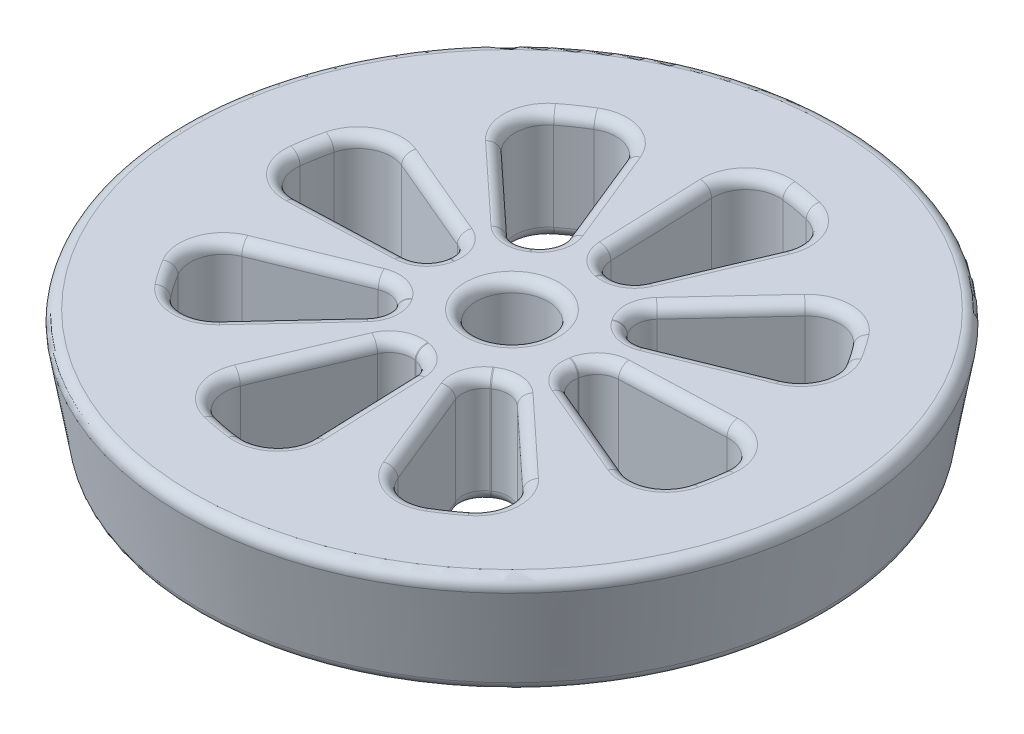
SolidWorks part; units mm, degrees
ref_plane "Front Plane" through (0, 0, 0) normal (0, 0, 1) x (1, 0, 0)
ref_plane "Top Plane" through (0, 0, 0) normal (0, 1, 0) x (1, 0, 0)
ref_plane "Right Plane" through (0, 0, 0) normal (1, 0, 0) x (0, 0, -1)
sketch "草圖1" plane through (0, 0, 0) normal (0, 1, 0) x (1, 0, 0)
  line L0 (-5.5912, 21.2777) -> (-1.9061, 7.2537)
  line L1 (4.3315, 6.1228) -> (12.7057, 17.9601)
  line L2 (0, 0) -> (12.7057, 17.9601) construction
  line L3 (0, 0) -> (-5.5912, 21.2777) construction
  circle A0 centre (0, 0) radius 30
  circle A1 centre (0, 0) radius 22
  circle A2 centre (0, 0) radius 3.25
  circle A3 centre (0, 0) radius 7.5
  arc A4 (-1.9061, 7.2537) -> (4.3315, 6.1228) centre (0, 0) cw
  arc A5 (-5.5912, 21.2777) -> (12.7057, 17.9601) centre (0, 0) ccw
  dimension "D1" = 60
  dimension "D2" = 8
  dimension "D3" = 6.5
  dimension "D4" = 15
  dimension "D5" = 50
extrude "填料-伸長1" add sketch "草圖1" along normal blind 10 contours A0 A1 | A3 A2
sketch "草圖2" plane through (0, 10, 0) normal (0, 1, 0) x (1, 0, 0)
  line L0 (-2.8233, 6.9483) -> (-8.2817, 20.3817)
  line L1 (-0.2766, 7.4949) -> (-0.8113, 21.985)
  line L2 (0, 0) -> (-0.8113, 21.985) construction
  line L3 (0, 0) -> (-8.2817, 20.3817) construction
  line L4 (5.1041, 5.4953) -> (14.9721, 16.1194)
  line L5 (2.9168, 6.9096) -> (8.556, 20.2681)
  line L6 (7.4949, 0.2766) -> (21.985, 0.8113)
  line L7 (6.9483, 2.8233) -> (20.3817, 8.2817)
  line L8 (5.4953, -5.1041) -> (16.1194, -14.9721)
  line L9 (6.9096, -2.9168) -> (20.2681, -8.556)
  line L10 (0.2766, -7.4949) -> (0.8113, -21.985)
  line L11 (2.8233, -6.9483) -> (8.2817, -20.3817)
  line L12 (-5.1041, -5.4953) -> (-14.9721, -16.1194)
  line L13 (-2.9168, -6.9096) -> (-8.556, -20.2681)
  line L14 (-7.4949, -0.2766) -> (-21.985, -0.8113)
  line L15 (-6.9483, -2.8233) -> (-20.3817, -8.2817)
  line L16 (-5.4953, 5.1041) -> (-16.1194, 14.9721)
  line L17 (-6.9096, 2.9168) -> (-20.2681, 8.556)
  circle A0 centre (0, 0) radius 22 construction
  arc A1 (-0.2766, 7.4949) -> (-2.8233, 6.9483) centre (0, 0) ccw
  arc A2 (-0.8113, 21.985) -> (-8.2817, 20.3817) centre (0, 0) ccw
  circle A3 centre (0, 0) radius 7.5 construction
  arc A4 (14.9721, 16.1194) -> (8.556, 20.2681) centre (0, 0) ccw
  arc A5 (5.1041, 5.4953) -> (2.9168, 6.9096) centre (0, 0) ccw
  arc A6 (21.985, 0.8113) -> (20.3817, 8.2817) centre (0, 0) ccw
  arc A7 (7.4949, 0.2766) -> (6.9483, 2.8233) centre (0, 0) ccw
  arc A8 (16.1194, -14.9721) -> (20.2681, -8.556) centre (0, 0) ccw
  arc A9 (5.4953, -5.1041) -> (6.9096, -2.9168) centre (0, 0) ccw
  arc A10 (0.8113, -21.985) -> (8.2817, -20.3817) centre (0, 0) ccw
  arc A11 (0.2766, -7.4949) -> (2.8233, -6.9483) centre (0, 0) ccw
  arc A12 (-14.9721, -16.1194) -> (-8.556, -20.2681) centre (0, 0) ccw
  arc A13 (-5.1041, -5.4953) -> (-2.9168, -6.9096) centre (0, 0) ccw
  arc A14 (-21.985, -0.8113) -> (-20.3817, -8.2817) centre (0, 0) ccw
  arc A15 (-7.4949, -0.2766) -> (-6.9483, -2.8233) centre (0, 0) ccw
  arc A16 (-16.1194, 14.9721) -> (-20.2681, 8.556) centre (0, 0) ccw
  arc A17 (-5.4953, 5.1041) -> (-6.9096, 2.9168) centre (0, 0) ccw
  point P40 (0, 0)
  circle M7 centre (0, 0) radius 22
  dimension "D1" = 20
  dimension "D2" = 8
extrude "填料-伸長3" add sketch "草圖2" against normal through all contours A5 L4 L5 M7 | A1 L1 L0 M7 | A17 L16 L17 M7 | A15 L14 L15 M7 | A13 L12 L13 M7 | A11 L10 L11 M7 | A9 L8 L9 M7 | A7 L6 L7 M7
fillet "圓角1" radius 3 16 edges at (20.2681, 5, 8.556) (16.1194, 5, 14.9721) (20.3817, 5, -8.2817) (8.556, 5, -20.2681) (21.985, 5, -0.8113) (14.9721, 5, -16.1194) (-8.2817, 5, -20.3817) (-0.8113, 5, -21.985) (-20.2681, 5, -8.556) (-16.1194, 5, -14.9721) (-20.3817, 5, 8.2817) (-21.985, 5, 0.8113) (-8.556, 5, 20.2681) (-14.9721, 5, 16.1194) (8.2817, 5, 20.3817) (0.8113, 5, 21.985)
fillet "圓角3" radius 2 16 edges at (-0.2766, 5, -7.4949) (2.9168, 5, -6.9096) (6.9483, 5, -2.8233) (5.1041, 5, -5.4953) (7.4949, 5, -0.2766) (6.9096, 5, 2.9168) (5.4953, 5, 5.1041) (2.8233, 5, 6.9483) (-2.9168, 5, 6.9096) (0.2766, 5, 7.4949) (-6.9483, 5, 2.8233) (-5.1041, 5, 5.4953) (-6.9096, 5, -2.9168) (-7.4949, 5, 0.2766) (-2.8233, 5, -6.9483) (-5.4953, 5, -5.1041)
sketch "草圖3" plane through (0, 10, 0) normal (0, 1, 0) x (1, 0, 0)
  circle A0 centre (0, 0) radius 30
  circle A1 centre (0, 0) radius 58.0891
extrude "除料-伸長1" cut sketch "草圖3" against normal through all draft 10 draft outward yes
fillet "圓角4" radius 1 120 edges at (0, 0, 28.2367) (5.7905, 0, -5.5818) (9.5443, 10, -10.2757) (9.5443, 0, -10.2757) (15.0935, 0, -14.7024) (18.1061, 0, -12.4968) (19.0998, 0, -8.8978) (12.9928, 0, -5.2793) (12.9928, 10, -5.2793) (7.2727, 0, -3.4344) (6.1725, 0, -4.2603) (8.0414, 0, 0.1476) (14.0148, 10, -0.5172) (14.0148, 0, -0.5172) (21.0689, 0, 0.2766) (3.9664, 0, -21.6395) (19.7973, 0, 7.2139) (12.9203, 0, 5.4542) (12.9203, 10, 5.4542) (7.571, 0, 2.7141) (7.3771, 0, 1.3522) (5.5818, 0, 5.7905) (10.2757, 10, 9.5443) (10.2757, 0, 9.5443) (14.7024, 0, 15.0935) (8.8978, 0, 19.0998) (5.2793, 0, 12.9928) (5.2793, 10, 12.9928) (3.4344, 0, 7.2727) (4.2603, 0, 6.1725) (-0.1476, 0, 8.0414) (0.5172, 10, 14.0148) (0.5172, 0, 14.0148) (-0.2766, 0, 21.0689) (-7.2139, 0, 19.7973) (-5.4542, 0, 12.9203) (-5.4542, 10, 12.9203) (-2.7141, 0, 7.571) (-1.3522, 0, 7.3771) (-5.7905, 0, 5.5818) (-9.5443, 10, 10.2757) (-9.5443, 0, 10.2757) (-15.0935, 0, 14.7024) (-19.0998, 0, 8.8978) (-12.9928, 0, 5.2793) (-12.9928, 10, 5.2793) (-7.2727, 0, 3.4344) (-6.1725, 0, 4.2603) (-5.5818, 0, -5.7905) (-10.2757, 10, -9.5443) (-10.2757, 0, -9.5443) (-14.7024, 0, -15.0935) (-8.8978, 0, -19.0998) (-5.2793, 0, -12.9928) (-5.2793, 10, -12.9928) (-3.4344, 0, -7.2727) (-4.2603, 0, -6.1725) (0.1476, 0, -8.0414) (-0.5172, 10, -14.0148) (-0.5172, 0, -14.0148) (0.2766, 0, -21.0689) (7.2139, 0, -19.7973) (5.4542, 0, -12.9203) (5.4542, 10, -12.9203) (2.7141, 0, -7.571) (1.3522, 0, -7.3771) (-8.0414, 0, -0.1476) (-14.0148, 10, 0.5172) (-14.0148, 0, 0.5172) (-21.0689, 0, -0.2766) (-19.7973, 0, -7.2139) (-12.9203, 0, -5.4542) (-12.9203, 10, -5.4542) (-7.571, 0, -2.7141) (-7.3771, 0, -1.3522) (0, 0, 3.25) (0, 10, 3.25) (0, 10, 30) (-21.0689, 10, -0.2766) (-8.0414, 10, -0.1476) (-7.3771, 10, -1.3522) (-7.571, 10, -2.7141) (-19.7973, 10, -7.2139) (18.1061, 10, -12.4968) (3.9664, 10, -21.6395) (2.7141, 10, -7.571) (7.2139, 10, -19.7973) (0.2766, 10, -21.0689) (0.1476, 10, -8.0414) (1.3522, 10, -7.3771) (-3.4344, 10, -7.2727) (-8.8978, 10, -19.0998) (-14.7024, 10, -15.0935) (-5.5818, 10, -5.7905) (-4.2603, 10, -6.1725) (-19.0998, 10, 8.8978) (-15.0935, 10, 14.7024) (-5.7905, 10, 5.5818) (-6.1725, 10, 4.2603) (-7.2727, 10, 3.4344) (-7.2139, 10, 19.7973) (-0.2766, 10, 21.0689) (-0.1476, 10, 8.0414) (-1.3522, 10, 7.3771) (-2.7141, 10, 7.571) (8.8978, 10, 19.0998) (14.7024, 10, 15.0935) (5.5818, 10, 5.7905) (4.2603, 10, 6.1725) (3.4344, 10, 7.2727) (19.7973, 10, 7.2139) (21.0689, 10, 0.2766) (8.0414, 10, 0.1476) (7.3771, 10, 1.3522) (7.571, 10, 2.7141) (19.0998, 10, -8.8978) (15.0935, 10, -14.7024) (5.7905, 10, -5.5818) (6.1725, 10, -4.2603) (7.2727, 10, -3.4344)
